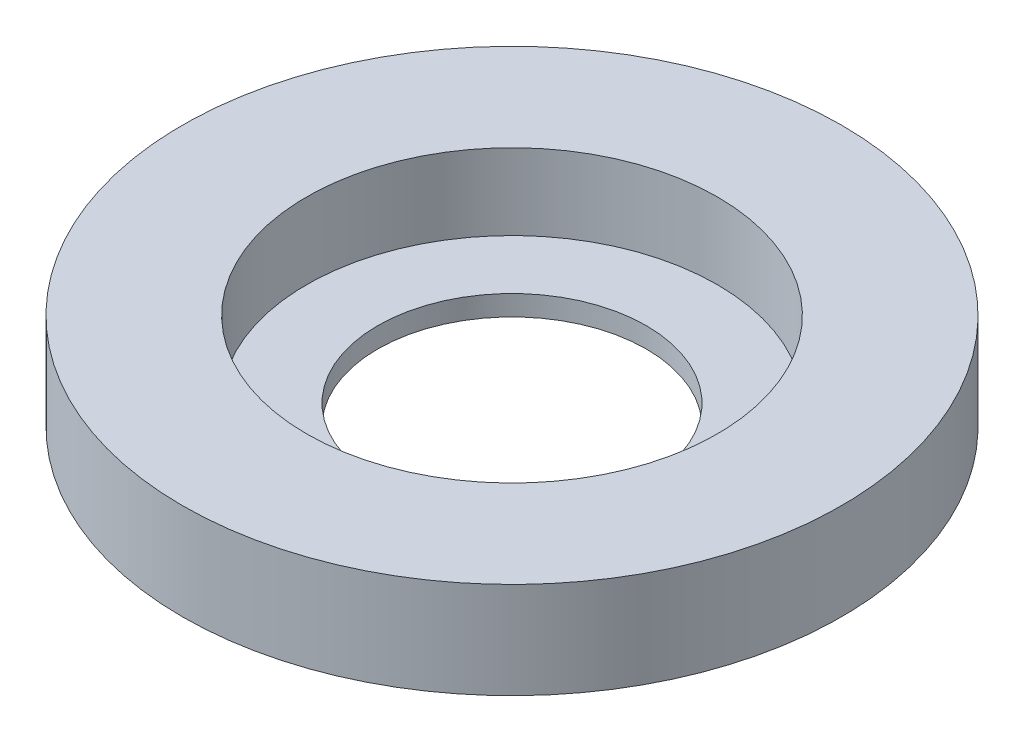
SolidWorks part; units mm, degrees
ref_plane "Front Plane" through (0, 0, 0) normal (0, 0, 1) x (1, 0, 0)
ref_plane "Top Plane" through (0, 0, 0) normal (0, 1, 0) x (1, 0, 0)
ref_plane "Right Plane" through (0, 0, 0) normal (1, 0, 0) x (0, 0, -1)
sketch "Sketch1" plane through (0, 0, 0) normal (0, 0, 1) x (1, 0, 0)
  line L0 (0, 0) -> (0, 7.6914) construction
  line L1 (5.3, 0) -> (13, 0)
  line L2 (13, 0) -> (13, 3.8)
  line L3 (13, 3.8) -> (8.1, 3.8)
  line L4 (8.1, 3.8) -> (8.1, 0.8)
  line L5 (8.1, 0.8) -> (5.3, 0.8)
  line L6 (5.3, 0.8) -> (5.3, 0)
  dimension "D1" = 0.8
  dimension "D2" = 26
  dimension "D3" = 3.8
  dimension "D4" = 10.6
  dimension "D5" = 16.2
revolve "Revolve1" add sketch "Sketch1" angle 360 about L0
